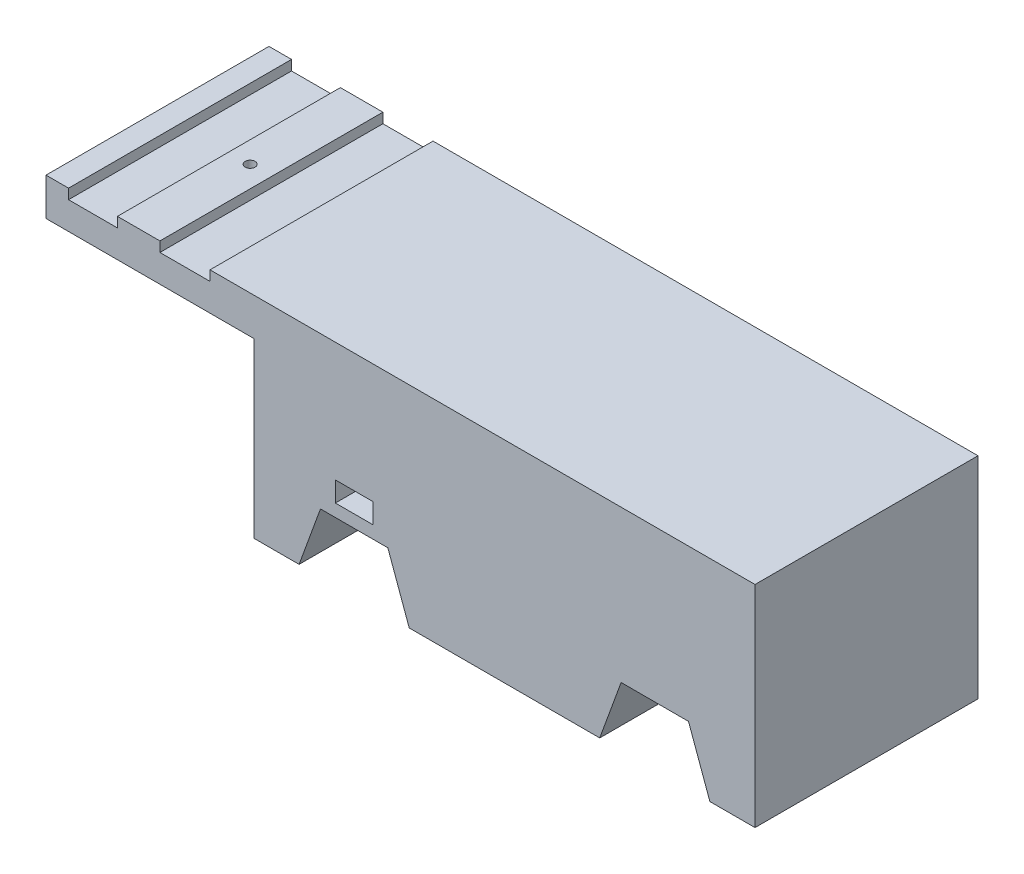
SolidWorks part; units mm, degrees
ref_plane "Front Plane" through (0, 0, 0) normal (0, 0, 1) x (1, 0, 0)
ref_plane "Top Plane" through (0, 0, 0) normal (0, 1, 0) x (1, 0, 0)
ref_plane "Right Plane" through (0, 0, 0) normal (1, 0, 0) x (0, 0, -1)
sketch "Sketch1" plane through (0, 0, 0) normal (0, 0, 1) x (1, 0, 0)
  line L0 (-283, 0) -> (0, 0)
  line L1 (0, 0) -> (0, 15)
  line L2 (0, 15) -> (-217.53, 15)
  line L3 (-217.53, 15) -> (-217.53, 11)
  line L4 (-217.53, 11) -> (-237.53, 11)
  line L5 (-237.53, 11) -> (-237.53, 15)
  line L6 (-237.53, 15) -> (-254.5, 15)
  line L7 (-254.5, 15) -> (-254.5, 11)
  line L8 (-254.5, 11) -> (-274, 11)
  line L9 (-274, 11) -> (-274, 15)
  line L10 (-274, 15) -> (-283, 15)
  line L11 (-283, 15) -> (-283, 0)
  dimension "D1" = 283
  dimension "D2" = 217.53
  dimension "D3" = 9
  dimension "D4" = 19.5
  dimension "D5" = 16.97
  dimension "D6" = 20
  dimension "D7" = 15
  dimension "D8" = 4
extrude "Boss-Extrude1" add sketch "Sketch1" along normal blind 89
sketch "Sketch2" plane through (0, 15, 0) normal (0, 1, 0) x (1, 0, 0)
  line L0 (-283, -44.5) -> (-71.3341, -44.5) construction
  line L1 (-283, -89) -> (-283, 0) construction
  line L2 (-246.015, 0) -> (-246.015, -93.7366) construction
  line L3 (-237.53, 0) -> (-254.5, 0) construction
  circle A0 centre (-246.015, -44.5) radius 2
  dimension "D1" = 4
extrude "Cut-Extrude1" cut sketch "Sketch2" against normal blind 26
sketch "Sketch3" plane through (0, 0, 0) normal (0, 0, -1) x (-1, 0, 0)
  line L0 (213, -0.0192) -> (213, -74.1) construction
  line L1 (213, -74.1) -> (-6.6499, -74.1) construction
  line L2 (283, 0) -> (0, 0) construction
  line L3 (0, 0) -> (0, 15) construction
  line L4 (0, 0) -> (0, -61.6)
  line L5 (180, -61.6) -> (200, -61.6) construction
  line L6 (200, -61.6) -> (200, 7.5)
  line L7 (146.5515, -45.6) -> (173.4485, -45.6)
  line L8 (173.4485, -45.6) -> (181.9825, -69.0468)
  line L9 (160, -61.6) -> (160, -80.8536) construction
  line L10 (146.5515, -45.6) -> (138.0175, -69.0468)
  line L11 (140, -61.6) -> (60, -61.6) construction
  line L12 (0, -61.6) -> (200, -61.6) construction
  line L13 (100, -61.6) -> (100, 5.3066) construction
  line L14 (26.5515, -45.6) -> (18.0175, -69.0468)
  line L15 (53.4485, -45.6) -> (26.5515, -45.6)
  line L16 (53.4485, -45.6) -> (61.9825, -69.0468)
  line L17 (20, -61.6) -> (0, -61.6) construction
  line L18 (0, 0) -> (0, 7.5)
  line L19 (0, 7.5) -> (200, 7.5)
  line L20 (0, -69.0468) -> (18.0175, -69.0468)
  line L21 (200, -69.0468) -> (200, -61.6)
  line L22 (0, -61.6) -> (0, -69.0468)
  line L24 (61.9825, -69.0468) -> (138.0175, -69.0468)
  line L25 (181.9825, -69.0468) -> (200, -69.0468)
  circle A0 centre (160, -61.6) radius 10.5 construction
  circle A1 centre (160, -61.6) radius 12.5 construction
  circle A2 centre (40, -61.6) radius 10.5 construction
  circle A3 centre (40, -61.6) radius 12.5 construction
  point P21 (160, -45.6)
  dimension "D3" = 25
  dimension "D4" = 21
  dimension "D1" = 74.1
  dimension "D2" = 213
  dimension "D5" = 160
  dimension "D6" = 16
  dimension "D7" = 110
  dimension "D8" = 20
  dimension "D9" = 200
extrude "Boss-Extrude2" add sketch "Sketch3" against normal up to surface (89 mm away) up to face at (-211.0933, 11.1667, 89)
ref_plane "Plane1" through (0, 0, 44.5) normal (0, 0, -1) x (-1, 0, 0)
sketch "Sketch4" plane through (0, 0, 44.5) normal (0, 0, -1) x (-1, 0, 0)
  line L0 (16.2365, -65.0468) -> (64.159, -65.0468)
  line L1 (64.159, -65.0468) -> (64.159, -38.3472)
  line L2 (64.159, -38.3472) -> (16.2365, -38.3472)
  line L3 (16.2365, -38.3472) -> (16.2365, -65.0468)
  line L4 (0, -69.0468) -> (18.0175, -69.0468) construction
  dimension "D1" = 4
extrude "Boss-Extrude3" add sketch "Sketch4" along normal mid plane 40
sketch "Sketch6" plane through (0, 0, 0) normal (0, 0, -1) x (-1, 0, 0)
  line L0 (213, -74.1) -> (-6.6499, -74.1) construction
  line L1 (213, -74.1) -> (-6.6499, -74.1)
  circle A0 centre (160, -61.6) radius 10.5 construction
  circle A1 centre (160, -61.6) radius 12.5 construction
  circle A2 centre (40, -61.6) radius 12.5 construction
  circle A3 centre (40, -61.6) radius 10.5 construction
  circle A4 centre (160, -61.6) radius 10.5
  circle A5 centre (160, -61.6) radius 12.5
  circle A6 centre (40, -61.6) radius 12.5
  circle A7 centre (40, -61.6) radius 10.5
sketch "Sketch7" plane through (0, 0, 24.5) normal (0, 0, -1) x (-1, 0, 0)
  circle A0 centre (40, -61.6) radius 2.5
  dimension "D1" = 5
extrude "Cut-Extrude2" cut sketch "Sketch7" against normal through all
sketch "Sketch9" plane through (0, 0, 0) normal (0, 0, -1) x (-1, 0, 0)
  line L0 (160, -61.6) -> (160, -9.1635) construction
  line L1 (152.5, -40.6) -> (167.5, -40.6)
  line L2 (152.5, -40.6) -> (152.5, -32.6)
  line L3 (152.5, -32.6) -> (167.5, -32.6)
  line L4 (167.5, -40.6) -> (167.5, -32.6)
  line L5 (152.5, -40.6) -> (167.5, -32.6) construction
  line L6 (152.5, -32.6) -> (167.5, -40.6) construction
  line L7 (146.5515, -45.6) -> (173.4485, -45.6) construction
  point P0 (160, -36.6)
  dimension "D1" = 15
  dimension "D2" = 8
  dimension "D3" = 5
extrude "Cut-Extrude3" cut sketch "Sketch9" against normal through all
sketch "Sketch8" plane through (0, -45.6, 0) normal (0, -1, 0) x (1, 0, 0)
  line L0 (-146.5515, 89) -> (-173.4485, 89) construction
  line L1 (-283, 0) -> (-200, 0) construction
  line L2 (0, 89) -> (0, 0) construction
  circle A0 centre (-160, 74) radius 2.5
  circle A1 centre (-160, 15) radius 2.5
  point P9 (0, 0)
  point P12 (0, 0)
  dimension "D1" = 5
  dimension "D3" = 5
  dimension "D2" = 15
  dimension "D4" = 15
  dimension "D5" = 160
  dimension "D6" = 160
extrude "Cut-Extrude4" cut sketch "Sketch8" against normal up to next
